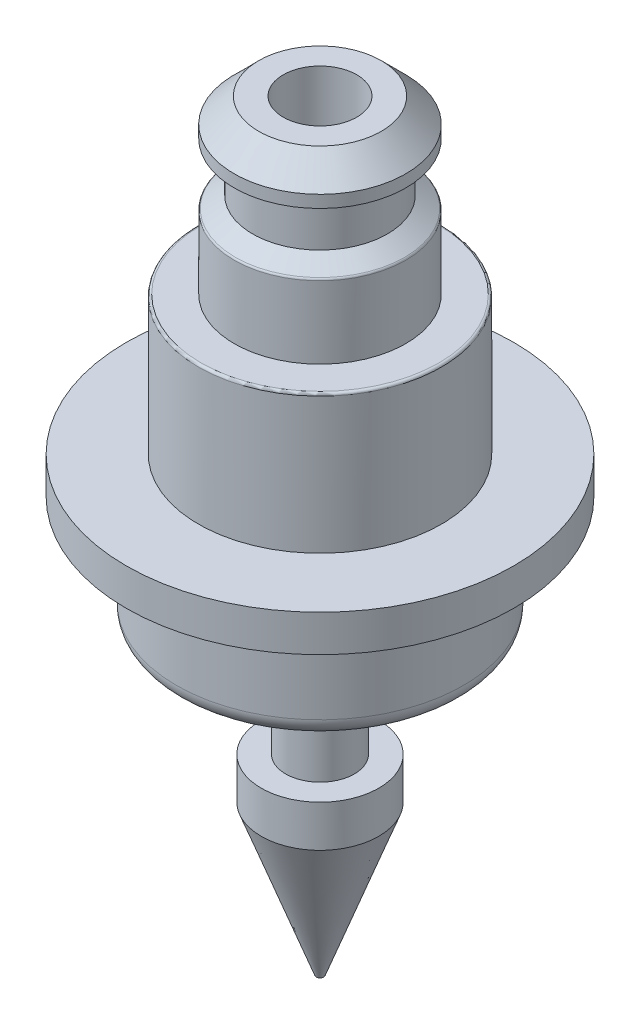
SolidWorks part; units mm, degrees
ref_plane "Front" through (0, 0, 0) normal (0, 0, 1) x (1, 0, 0)
ref_plane "Top" through (0, 0, 0) normal (0, 1, 0) x (1, 0, 0)
ref_plane "Right" through (0, 0, 0) normal (1, 0, 0) x (0, 0, -1)
sketch "Sketch1" plane through (0, 0, 0) normal (0, 0, 1) x (1, 0, 0)
  line L0 (0, 0) -> (0, 14.15) construction
  line L1 (0, 14.15) -> (1.5, 14.15) construction
  line L2 (1.5, 14.15) -> (1.5, 0) construction
  line L3 (1.5, 0) -> (0, 0) construction
  line L4 (1.5, 14.15) -> (2.5, 14.15)
  line L5 (2.5, 14.15) -> (3.5, 13.15)
  line L6 (3.5, 13.15) -> (3.5, 12.65)
  line L7 (3.5, 12.65) -> (2.75, 12.15)
  line L8 (2.75, 12.15) -> (2.75, 10.65)
  line L9 (2.75, 10.65) -> (3.5, 10.15)
  line L10 (3.5, 10.15) -> (3.5, 7.15)
  line L11 (3.5, 7.15) -> (4.955, 7.15)
  line L12 (4.955, 7.15) -> (4.955, 1.5)
  line L13 (4.955, 1.5) -> (7.9, 1.5)
  line L14 (7.9, 1.5) -> (7.9, 0)
  line L15 (7.9, 0) -> (5.85, 0)
  line L16 (5.85, 0) -> (5.85, -4.5)
  line L17 (5.85, -4.5) -> (1.4, -4.5)
  line L18 (3.5, 12.65) -> (3.5, 10.15) construction
  line L19 (2.75, 11.4) -> (3.5, 11.4) construction
  line L20 (1.4, -4.5) -> (1.4, -9.1)
  line L21 (1.4, -9.1) -> (2.4, -9.1)
  line L22 (2.4, -9.1) -> (2.4, -10.8)
  line L23 (2.4, -10.8) -> (0.15, -16.9)
  line L24 (0.15, -16.9) -> (0.15, 0)
  line L25 (0.15, 0) -> (1.5, 0)
  line L26 (1.5, 0) -> (1.5, 14.15)
  dimension "D1" = 5
  dimension "D2" = 7
  dimension "D3" = 3
  dimension "D4" = 5.5
  dimension "D5" = 12.65
  dimension "D6" = 15.8
  dimension "D7" = 11.7
  dimension "D8" = 4.5
  dimension "D9" = 1.5
  dimension "D10" = 9.91
  dimension "D11" = 7
  dimension "D12" = 1
  dimension "D13" = 1.5
  dimension "D14" = 4
  dimension "D15" = 2
  dimension "D16" = 0.3
  dimension "D17" = 2.8
  dimension "D18" = 4.8
  dimension "D19" = 1.7
  dimension "D20" = 7.8
  dimension "D21" = 12.4
revolve "Revolve1" add sketch "Sketch1" angle 360 about L0
fillet "Fillet1" radius 0.75 1 edges at (0, -4.5, -5.85)
fillet "Fillet2" radius 0.1 2 edges at (0, 10.15, -3.5) (0, 7.15, -4.955)
